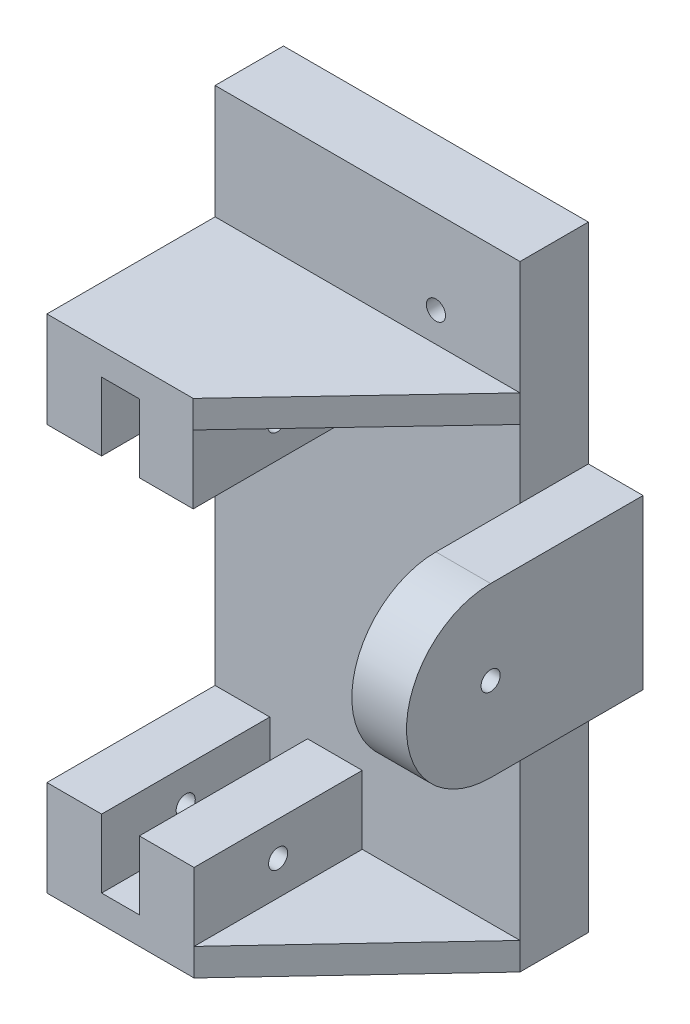
SolidWorks part; units mm, degrees
ref_plane "Plan de face" through (0, 0, 0) normal (0, 0, 1) x (1, 0, 0)
ref_plane "Plan de dessus" through (0, 0, 0) normal (0, 1, 0) x (1, 0, 0)
ref_plane "Plan de droite" through (0, 0, 0) normal (1, 0, 0) x (0, 0, -1)
sketch "Esquisse1" plane through (0, 0, 0) normal (0, 0, 1) x (1, 0, 0)
  line L0 (-6.15, 0) -> (-6.15, -6.15) construction
  line L1 (0, 0) -> (-22.3, 0)
  line L2 (0, 0) -> (0, -43)
  line L3 (0, -43) -> (-22.3, -43)
  line L4 (-22.3, 0) -> (-22.3, -43)
  line L5 (-6.15, -6.15) -> (0, -6.15) construction
  circle A0 centre (-6.15, -6.15) radius 2.45
  dimension "D1" = 22.3
  dimension "D2" = 43
  dimension "D3" = 6.15
  dimension "D4" = 6.15
extrude "Boss.-Extru.1" add sketch "Esquisse1" along normal blind 5
sketch "Esquisse2" plane through (0, 0, 5) normal (0, 0, 1) x (1, 0, 0)
  circle A0 centre (-6.15, -6.15) radius 2.45
  circle A1 centre (-6.15, -6.15) radius 0.7
extrude "Boss.-Extru.2" add sketch "Esquisse2" against normal blind 2.47
sketch "Esquisse3" plane through (0, 0, 5) normal (0, 0, 1) x (1, 0, 0)
  line L0 (-22.3, 0) -> (-22.3, -43) construction
  line L1 (-22.3, -38) -> (-18.3, -38)
  line L2 (-22.3, -38) -> (-22.3, -43)
  line L3 (-22.3, -43) -> (-18.3, -43)
  line L4 (-18.3, -38) -> (-18.3, -43)
  line L5 (-22.3, -43) -> (0, -43) construction
  line L6 (-18.3, -38) -> (-18.3, 0) construction
  line L7 (-15.54, -43) -> (-11.54, -43)
  line L8 (-15.54, -43) -> (-15.54, -38)
  line L9 (-15.54, -38) -> (-11.54, -38)
  line L10 (-11.54, -43) -> (-11.54, -38)
  line L11 (0, 0) -> (-22.3, 0) construction
  line L12 (-15.54, -38) -> (-15.54, 0) construction
  line L13 (-22.3, -15.32) -> (-18.3, -15.32)
  line L14 (-22.3, -15.32) -> (-22.3, -10.32)
  line L15 (-22.3, -10.32) -> (-18.3, -10.32)
  line L16 (-18.3, -15.32) -> (-18.3, -10.32)
  line L17 (-18.3, -15.32) -> (0, -15.32) construction
  line L18 (0, -43) -> (0, 0) construction
  line L19 (-18.3, -10.32) -> (0, -10.32) construction
  line L20 (-15.54, -15.32) -> (-11.6, -15.32)
  line L21 (-15.54, -15.32) -> (-15.54, -10.32)
  line L22 (-15.54, -10.32) -> (-11.6, -10.32)
  line L23 (-11.6, -15.32) -> (-11.6, -10.32)
  line L24 (-18.3, -38) -> (0, -38) construction
  dimension "D1" = 4
  dimension "D2" = 5
  dimension "D3" = 4
  dimension "D4" = 2.76
  dimension "D5" = 22.68
  dimension "D6" = 5
extrude "Boss.-Extru.3" add sketch "Esquisse3" along normal blind 12.3
sketch "Esquisse4" plane through (-22.3, 0, 0) normal (-1, 0, 0) x (0, 0, 1)
  line L0 (5, -10.32) -> (5, -15.32) construction
  line L1 (17.3, -15.32) -> (5, -15.32) construction
  line L2 (5, -15.32) -> (5, -38) construction
  line L3 (5, -38) -> (5, -43) construction
  line L4 (17.3, -43) -> (0, -43) construction
  line L5 (5, -12.82) -> (17.3, -12.82) construction
  line L6 (17.3, -10.32) -> (17.3, -15.32) construction
  line L7 (5, -40.5) -> (17.3, -40.5) construction
  line L8 (17.3, -38) -> (17.3, -43) construction
  circle A0 centre (11.15, -12.82) radius 0.7
  circle A1 centre (11.15, -40.5) radius 0.7
extrude "Enlèv. mat.-Extru.1" cut sketch "Esquisse4" against normal through all
sketch "Esquisse5" plane through (0, -43, 0) normal (0, -1, 0) x (1, 0, 0)
  line L0 (-22.3, 17.3) -> (-11.54, 17.3)
  line L1 (-11.54, 17.3) -> (0, 5)
  line L2 (0, 5) -> (0, 0)
  line L3 (0, 0) -> (-22.3, 0)
  line L4 (-22.3, 0) -> (-22.3, 17.3)
extrude "Boss.-Extru.4" add sketch "Esquisse5" along normal blind 2
sketch "Esquisse6" plane through (0, -10.32, 0) normal (0, 1, 0) x (1, 0, 0)
  line L0 (-22.3, -5) -> (-22.3, -17.3)
  line L1 (-22.3, -17.3) -> (-11.6, -17.3)
  line L2 (-11.6, -17.3) -> (0, -5)
  line L3 (0, -5) -> (-22.3, -5)
extrude "Boss.-Extru.5" add sketch "Esquisse6" along normal blind 2
sketch "Esquisse7" plane through (0, 0, 0) normal (1, 0, 0) x (0, 0, -1)
  line L0 (0, -21.47) -> (-11.15, -21.47) construction
  line L1 (0, -45) -> (0, 0) construction
  line L3 (-5, -15.32) -> (0, -15.32) construction
  line L4 (0, -27.62) -> (-5, -27.62) construction
  line L5 (-5, -43) -> (-5, -10.32) construction
  line L6 (-11.15, -21.47) -> (-11.15, -15.32) construction
  line L7 (-11.15, -15.32) -> (0, -15.32)
  line L8 (0, -15.32) -> (0, -27.62)
  line L9 (0, -27.62) -> (-11.15, -27.62)
  arc A0 (-11.15, -27.62) -> (-11.15, -15.32) centre (-11.15, -21.47) cw
  circle A1 centre (-11.15, -21.47) radius 0.7
  dimension "D1" = 6.15
  dimension "D2" = 11.15
  dimension "D3" = 6.15
extrude "Boss.-Extru.6" add sketch "Esquisse7" along normal blind 4
